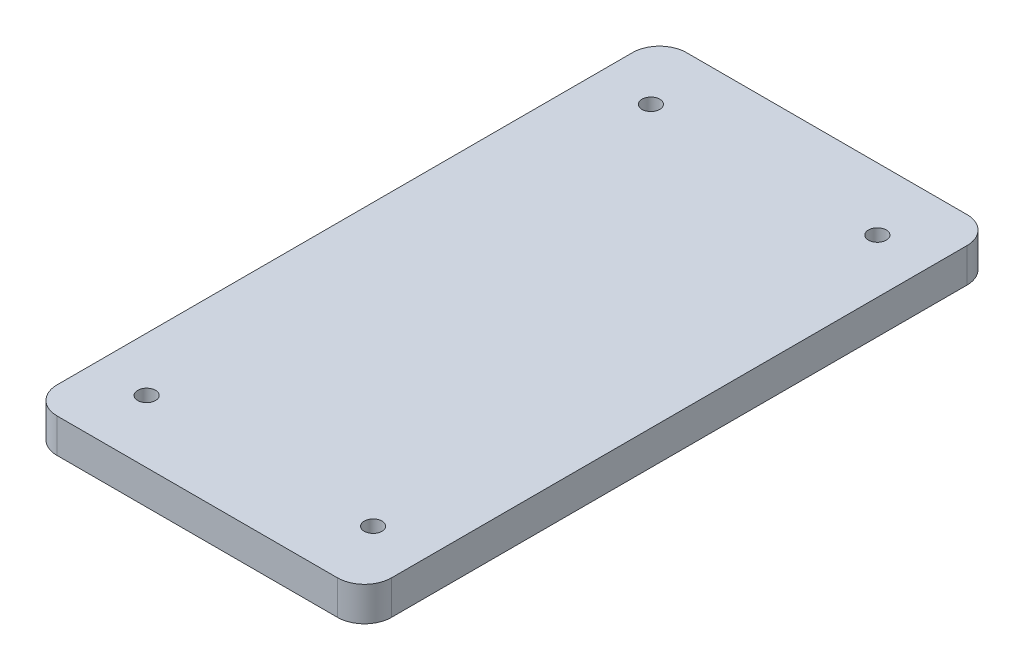
SolidWorks part; units mm, degrees
ref_plane "Alzado" through (0, 0, 0) normal (0, 0, 1) x (1, 0, 0)
ref_plane "Planta" through (0, 0, 0) normal (0, 1, 0) x (1, 0, 0)
ref_plane "Vista lateral" through (0, 0, 0) normal (1, 0, 0) x (0, 0, -1)
sketch "Croquis2" plane through (0, 0, 0) normal (0, 1, 0) x (1, 0, 0)
  line L0 (31, 116.7) -> (31, 0) construction
  line L1 (0, 0) -> (62, 0)
  line L2 (0, 0) -> (0, 116.7)
  line L3 (0, 116.7) -> (62, 116.7)
  line L4 (62, 0) -> (62, 116.7)
  line L5 (0, 58.35) -> (62, 58.35) construction
  line L6 (10, 11.6) -> (52, 11.6) construction
  line L7 (10, 105.1) -> (52, 105.1) construction
  line L8 (10, 105.1) -> (10, 11.6) construction
  circle A0 centre (10, 11.6) radius 1.65
  circle A1 centre (52, 11.6) radius 1.65
  circle A2 centre (10, 105.1) radius 1.65
  circle A3 centre (52, 105.1) radius 1.65
  point P15 (31, 11.6)
  dimension "D3" = 3.3
  dimension "D4" = 3.3
  dimension "D1" = 116.7
  dimension "D2" = 62
  dimension "D5" = 42
  dimension "D6" = 93.5
extrude "Saliente-Extruir1" add sketch "Croquis2" along normal blind 6.35
fillet "Redondeo2" radius 5 4 edges at (0, 3.175, -116.7) (62, 3.175, -116.7) (62, 3.175, 0) (0, 3.175, 0)
